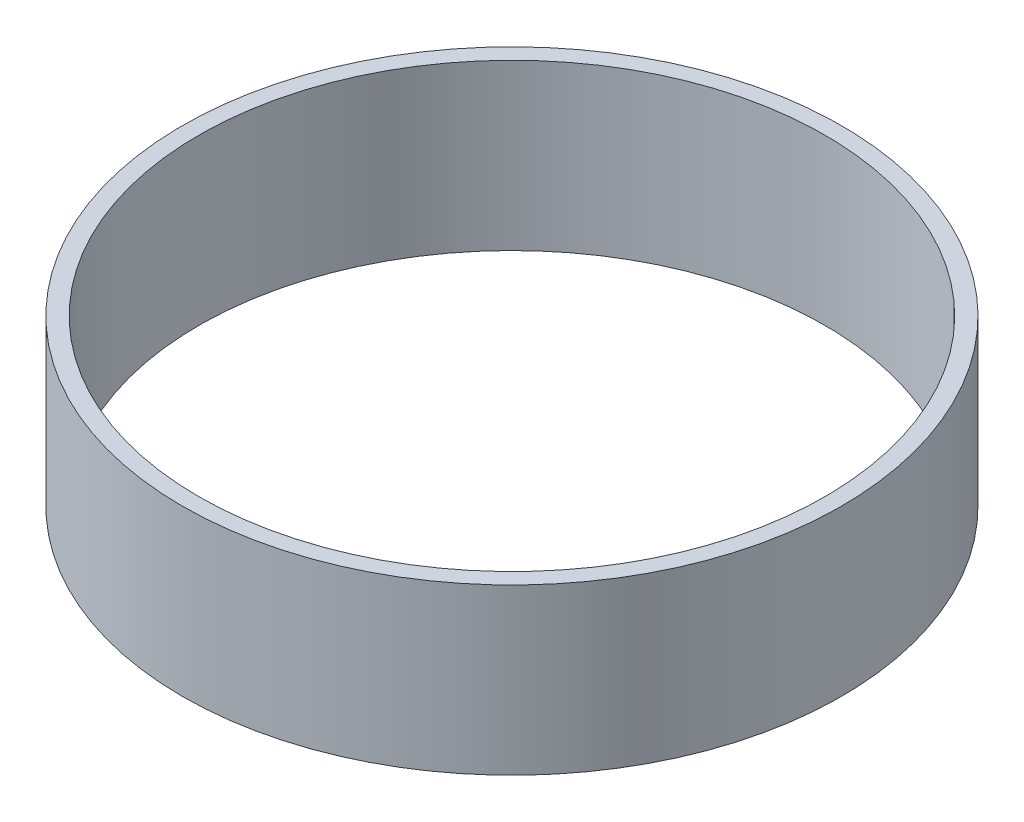
SolidWorks part; units mm, degrees
ref_plane "Front Plane" through (0, 0, 0) normal (0, 0, 1) x (1, 0, 0)
ref_plane "Top Plane" through (0, 0, 0) normal (0, 1, 0) x (1, 0, 0)
ref_plane "Right Plane" through (0, 0, 0) normal (1, 0, 0) x (0, 0, -1)
sketch "Sketch1" plane through (0, 0, 0) normal (0, 1, 0) x (1, 0, 0)
  circle A0 centre (0, 0) radius 400
  circle A1 centre (0, 0) radius 380
  dimension "D1" = 800
  dimension "D2" = 760
extrude "Boss-Extrude1" add sketch "Sketch1" along normal blind 200
